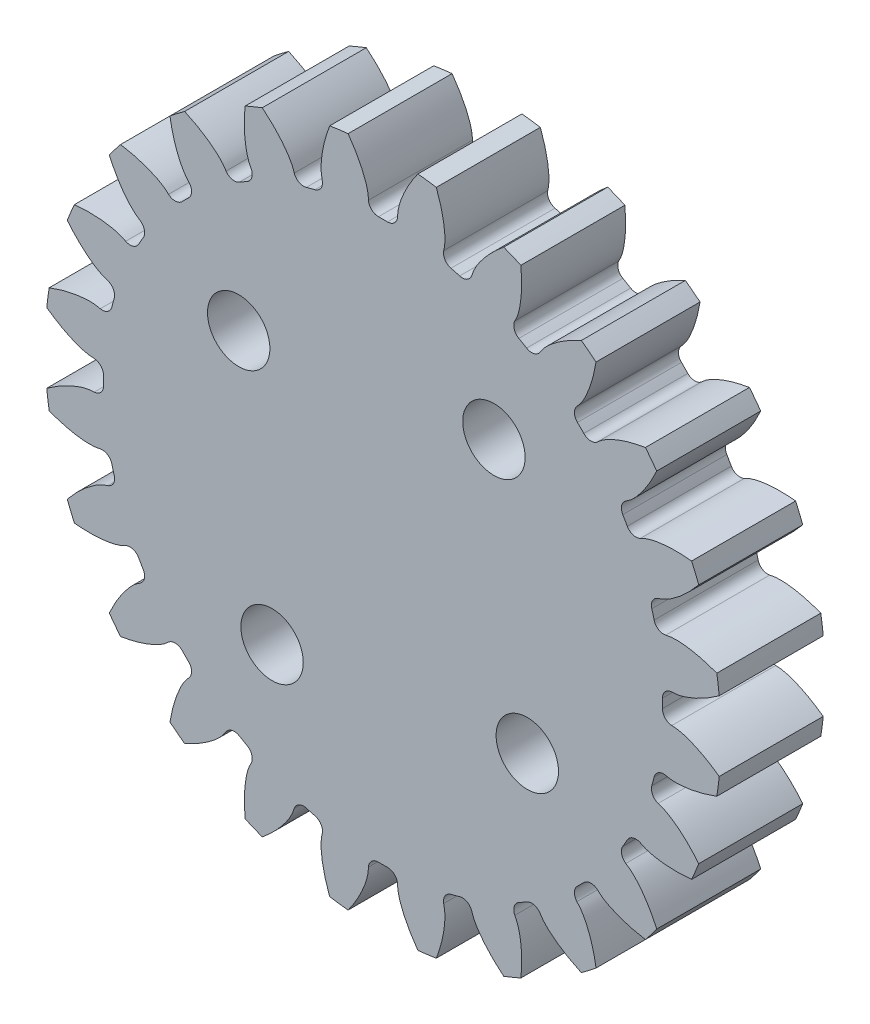
SolidWorks part; units mm, degrees
material "Vero PureWhite"
ref_plane "前视基准面" through (0, 0, 0) normal (0, 0, 1) x (1, 0, 0)
ref_plane "上视基准面" through (0, 0, 0) normal (0, 1, 0) x (1, 0, 0)
ref_plane "右视基准面" through (0, 0, 0) normal (1, 0, 0) x (0, 0, -1)
other "Configuration Table"
ref_axis "Axis1" through (0, 0, -88.99) along (0, 0, 1)
sketch "草图1" plane through (0, 0, 0) normal (0, 0, 1) x (1, 0, 0)
  circle A0 centre (0, 0) radius 13
extrude "LaShenA" add sketch "草图1" along normal blind 4
sketch "SketchA" plane through (0, 0, 4) normal (0, 0, 1) x (1, 0, 0)
  line L0 (0, 0) -> (0, 13) construction
  arc A0 (0.1732, 10.7486) -> (-0.1732, 10.7486) centre (0, 0) ccw
  arc A1 (1.7936, 13.4924) -> (-1.7936, 13.4924) centre (0, 0) ccw
  arc A2 (-0.1732, 10.7486) -> (-0.5586, 11.1053) centre (-0.1793, 11.1286) cw
  arc A3 (0.5586, 11.1053) -> (0.1732, 10.7486) centre (0.1793, 11.1286) cw
  circle A4 centre (0, 0) radius 11.2763 construction
  circle A5 centre (0, 0) radius 13 construction
  circle A6 centre (0, 0) radius 10.75 construction
  circle A7 centre (0, 0) radius 12 construction
  spline S0 degree 3 poles (0.5586, 11.1053) (0.5618, 11.1578) (0.5667, 11.2415) (0.5795, 11.3389) (0.5917, 11.3999) (0.6025, 11.4482) (0.6165, 11.5037) (0.6339, 11.5661) (0.6552, 11.6353) (0.6807, 11.7112) (0.7108, 11.7936) (0.7458, 11.8822) (0.786, 11.9769) (0.8319, 12.0775) (0.8838, 12.1837) (0.9418, 12.2952) (1.0065, 12.4119) (1.078, 12.5335) (1.1567, 12.6596) (1.2429, 12.79) (1.3368, 12.9243) (1.4386, 13.0623) (1.5886, 13.2548) (1.7092, 13.3975) (1.7936, 13.4924) knots 0.119767 0.119767 0.119767 0.119767 0.170317 0.200988 0.214489 0.230444 0.248855 0.26972 0.29304 0.318814 0.347044 0.377728 0.410866 0.44646 0.484508 0.525011 0.567969 0.613381 0.661248 0.71157 0.764347 0.819578 0.877264 1 1 1 1
  spline S1 degree 3 poles (-0.5586, 11.1053) (-0.5618, 11.1578) (-0.5667, 11.2415) (-0.5795, 11.3389) (-0.5917, 11.3999) (-0.6025, 11.4482) (-0.6165, 11.5037) (-0.6339, 11.5661) (-0.6552, 11.6353) (-0.6807, 11.7112) (-0.7108, 11.7936) (-0.7458, 11.8822) (-0.786, 11.9769) (-0.8319, 12.0775) (-0.8838, 12.1837) (-0.9418, 12.2952) (-1.0065, 12.4119) (-1.078, 12.5335) (-1.1567, 12.6596) (-1.2429, 12.79) (-1.3368, 12.9243) (-1.4386, 13.0623) (-1.5886, 13.2548) (-1.7092, 13.3975) (-1.7936, 13.4924) knots 0.119767 0.119767 0.119767 0.119767 0.170317 0.200988 0.214489 0.230444 0.248855 0.26972 0.29304 0.318814 0.347044 0.377728 0.410866 0.44646 0.484508 0.525011 0.567969 0.613381 0.661248 0.71157 0.764347 0.819578 0.877264 1 1 1 1
  dimension "D1" = 0.38
  dimension "Db" = 22.5526
  dimension "Da" = 26
  dimension "Df" = 21.5
  dimension "Dn" = 24
extrude "Cut-ExtrudeA" cut sketch "SketchA" against normal blind 30
pattern_circular "www.KYTool.cn" count 24 over 360 about axis through (0, 0, -88.99) along (0, 0, 1) of "Cut-ExtrudeA"
sketch "草图3" plane through (0, 0, 0) normal (0, 0, -1) x (-1, 0, 0)
  circle A0 centre (0, 0) radius 10.375 construction
  circle A1 centre (0, 0) radius 10.375
extrude "切除-拉伸2" cut sketch "草图3" against normal blind 2
hole_wizard "M2 间隙孔2" positions "草图7" profile "草图6" hole size "M2" standard "GB" end condition up to next
sketch "草图7" plane through (0, 0, 4) normal (0, 0, 1) x (1, 0, 0)
  line L3 (-5.5495, 4.2665) -> (-4.2665, -5.5495)
  line L4 (-4.2665, -5.5495) -> (5.5495, -4.2665)
  line L5 (5.5495, -4.2665) -> (4.2665, 5.5495)
  line L6 (4.2665, 5.5495) -> (-5.5495, 4.2665)
  circle A0 centre (0, 0) radius 7 construction
  point P0 (195.4366, 197.4945)
  point P1 (-5.5495, 4.2665)
  point P5 (4.2665, 5.5495)
  point P8 (-4.2665, -5.5495)
  point P11 (5.5495, -4.2665)
  dimension "D2" = 14
sketch "草图6" plane through (195.4366, 197.4945, 4) normal (1, 0, 0) x (0, -1, 0)
  line L0 (0, 0) -> (0, 4)
  line L1 (0, 4) -> (1.2, 4)
  line L2 (1.2, 4) -> (1.2, 0)
  line L5 (1.2, 0) -> (0, 0)
  line L11 (0, -6.35) -> (0, 107.95) construction
  dimension "通孔孔直径" = 2.4
  dimension "通孔孔深度" = 4
